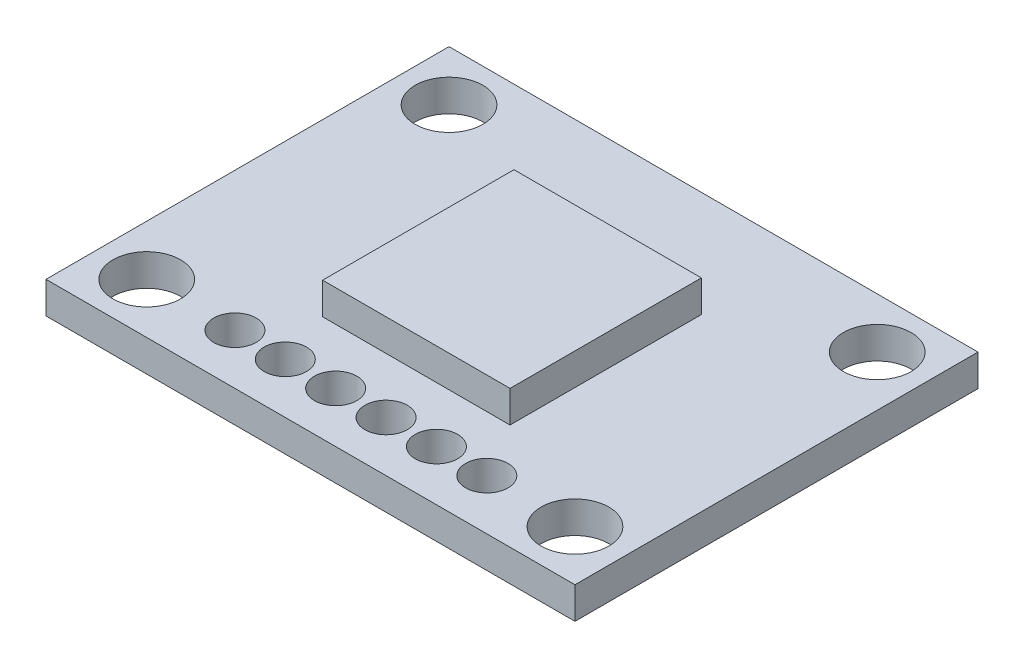
SolidWorks part; units mm, degrees
ref_plane "Front" through (0, 0, 0) normal (0, 0, 1) x (1, 0, 0)
ref_plane "Top" through (0, 0, 0) normal (0, 1, 0) x (1, 0, 0)
ref_plane "Right" through (0, 0, 0) normal (1, 0, 0) x (0, 0, -1)
sketch "Sketch1" plane through (0, 0, 0) normal (0, 1, 0) x (1, 0, 0)
  line L0 (0, 0) -> (0, 10.16) construction
  line L1 (-13.335, -10.16) -> (13.335, -10.16)
  line L2 (-13.335, -10.16) -> (-13.335, 10.16)
  line L3 (-13.335, 10.16) -> (13.335, 10.16)
  line L4 (13.335, -10.16) -> (13.335, 10.16)
  line L5 (-13.335, -10.16) -> (13.335, 10.16) construction
  line L6 (-13.335, 10.16) -> (13.335, -10.16) construction
  line L7 (0, 0) -> (13.335, 0) construction
  line L8 (-10.795, -7.62) -> (10.795, -7.62) construction
  circle A0 centre (-10.795, 7.62) radius 1.7078
  circle A1 centre (10.795, 7.62) radius 1.7078
  circle A2 centre (10.795, -7.62) radius 1.7078
  circle A3 centre (-10.795, -7.62) radius 1.7078
  circle A4 centre (-1.27, -7.62) radius 1.07
  circle A5 centre (-3.81, -7.62) radius 1.07
  circle A6 centre (-6.35, -7.62) radius 1.07
  circle A7 centre (6.35, -7.62) radius 1.07
  circle A8 centre (3.81, -7.62) radius 1.07
  circle A9 centre (1.27, -7.62) radius 1.07
  point P0 (0, 0)
  point P14 (10.795, -7.62)
  point P15 (-10.795, -7.62)
  dimension "D1" = 20.32
  dimension "D2" = 26.67
  dimension "D3" = 21.59
  dimension "D4" = 15.24
  dimension "D6" = 2.54
  dimension "D5" = 3
extrude "Boss-Extrude1" add sketch "Sketch1" along normal blind 1.6
sketch "Sketch2" plane through (0, 1.6, 0) normal (0, 1, 0) x (1, 0, 0)
  line L1 (-4.7249, -4.8236) -> (4.7249, -4.8236)
  line L2 (-4.7249, -4.8236) -> (-4.7249, 4.8236)
  line L3 (-4.7249, 4.8236) -> (4.7249, 4.8236)
  line L4 (4.7249, -4.8236) -> (4.7249, 4.8236)
  line L5 (-4.7249, -4.8236) -> (4.7249, 4.8236) construction
  line L6 (-4.7249, 4.8236) -> (4.7249, -4.8236) construction
  point P0 (0, 0)
extrude "Boss-Extrude2" add sketch "Sketch2" along normal blind 1.6
